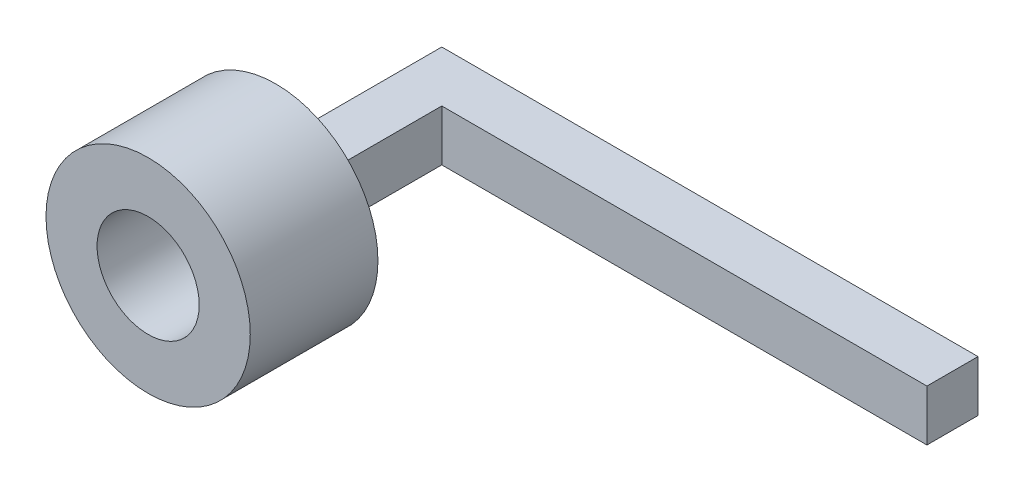
SolidWorks part; units mm, degrees
ref_plane "Front Plane" through (0, 0, 0) normal (0, 0, 1) x (1, 0, 0)
ref_plane "Top Plane" through (0, 0, 0) normal (0, 1, 0) x (1, 0, 0)
ref_plane "Right Plane" through (0, 0, 0) normal (1, 0, 0) x (0, 0, -1)
sketch "Sketch1" plane through (0, 0, 0) normal (0, 0, 1) x (1, 0, 0)
  circle A1 centre (0, 0) radius 2
  dimension "D2" = 4
extrude "Boss-Extrude1" add sketch "Sketch1" along normal blind 2.5
shell "Shell1" thickness 1
sketch "Sketch2" plane through (0, 0, 0) normal (0, 0, -1) x (-1, 0, 0)
  line L1 (0.5, -0.5) -> (-0.5, -0.5)
  line L2 (0.5, -0.5) -> (0.5, 0.5)
  line L3 (0.5, 0.5) -> (-0.5, 0.5)
  line L4 (-0.5, -0.5) -> (-0.5, 0.5)
  line L5 (0.5, -0.5) -> (-0.5, 0.5) construction
  line L6 (0.5, 0.5) -> (-0.5, -0.5) construction
  point P0 (0, 0)
  dimension "D1" = 1
  dimension "D2" = 1
extrude "Boss-Extrude2" add sketch "Sketch2" along normal blind 3.75
sketch "Sketch3" plane through (0.5, 0, 0) normal (1, 0, 0) x (0, 0, -1)
  line L0 (3.75, -0.5) -> (0, -0.5) construction
  line L1 (3.75, 0.5) -> (2.75, 0.5)
  line L2 (3.75, 0.5) -> (3.75, -0.5)
  line L3 (3.75, -0.5) -> (2.75, -0.5)
  line L4 (2.75, 0.5) -> (2.75, -0.5)
  dimension "D1" = 1
extrude "Boss-Extrude3" add sketch "Sketch3" along normal blind 9.5
